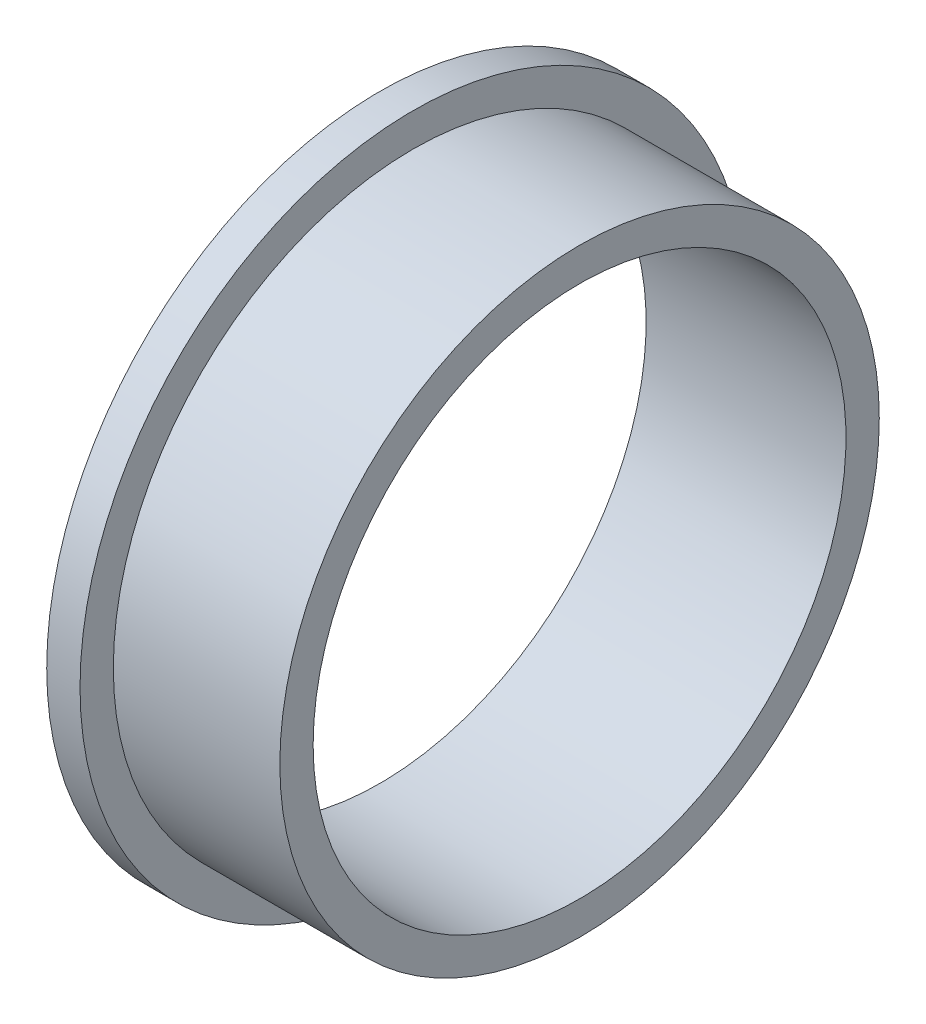
SolidWorks part; units mm, degrees
material "PPS"
ref_plane "Front Plane" through (0, 0, 0) normal (0, 0, 1) x (1, 0, 0)
ref_plane "Top Plane" through (0, 0, 0) normal (0, 1, 0) x (1, 0, 0)
ref_plane "Right Plane" through (0, 0, 0) normal (1, 0, 0) x (0, 0, -1)
sketch "Sketch1" plane through (0, 0, 0) normal (0, 1, 0) x (1, 0, 0)
  line L0 (-2, 16) -> (10, 16)
  line L1 (10, 16) -> (10, 18)
  line L2 (10, 18) -> (0, 18)
  line L4 (0, 0) -> (16.3244, 0) construction
  line L5 (0, 18) -> (0, 20)
  line L6 (0, 20) -> (-2, 20)
  line L7 (-2, 20) -> (-2, 16)
  dimension "D1" = 12
  dimension "D2" = 16
  dimension "D3" = 18
  dimension "D4" = 20
  dimension "D5" = 2
revolve "Revolve1" add sketch "Sketch1" angle 360 about L4
